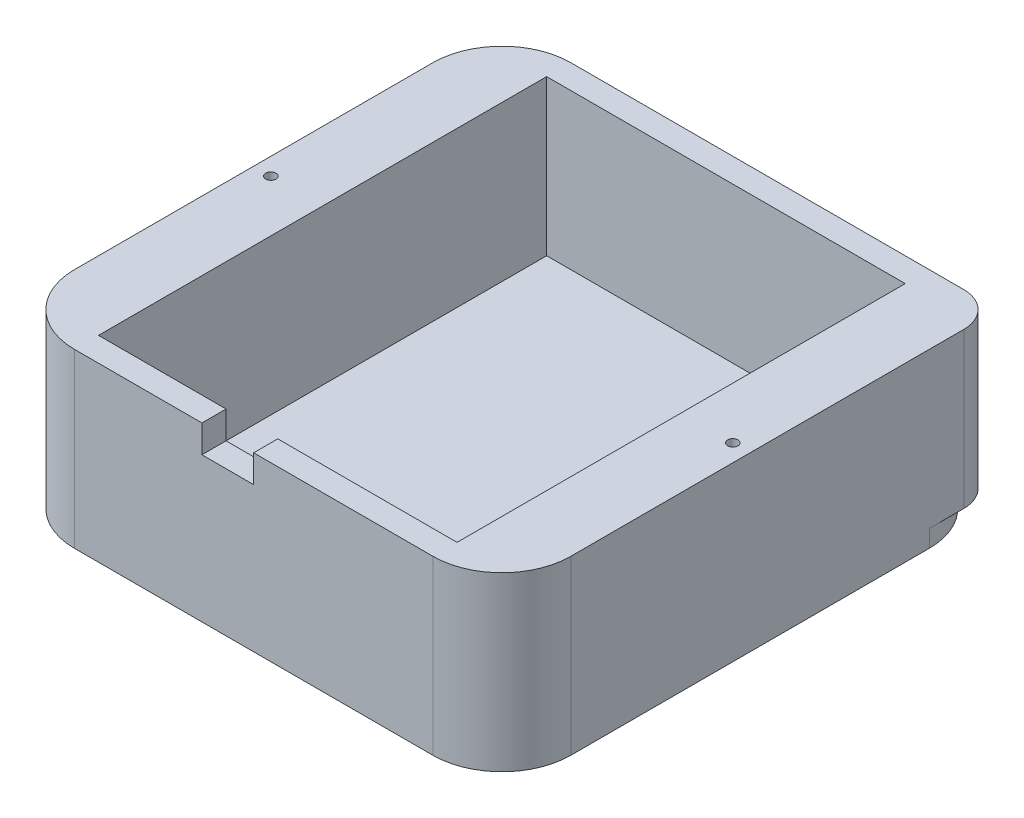
SolidWorks part; units mm, degrees
ref_plane "Front Plane" through (0, 0, 0) normal (0, 0, 1) x (1, 0, 0)
ref_plane "Top Plane" through (0, 0, 0) normal (0, 1, 0) x (1, 0, 0)
ref_plane "Right Plane" through (0, 0, 0) normal (1, 0, 0) x (0, 0, -1)
sketch "Sketch1" plane through (0, 0, 0) normal (0, 1, 0) x (1, 0, 0)
  line L1 (-72, 72) -> (72, 72)
  line L2 (-72, 72) -> (-72, -72)
  line L3 (-72, -72) -> (72, -72)
  line L4 (72, 72) -> (72, -72)
  point P0 (0, 0)
  dimension "D1" = 144
  dimension "D2" = 72
  dimension "D3" = 72
extrude "Boss-Extrude1" add sketch "Sketch1" along normal blind 5
fillet "Fillet1" radius 20 4 edges at (-72, 2.5, -72) (72, 2.5, -72) (-72, 2.5, 72) (72, 2.5, 72)
sketch "Sketch2" plane through (0, 5, 0) normal (0, 1, 0) x (1, 0, 0)
  line L0 (0, 72) -> (0, -72) construction
  line L2 (-52, -65) -> (-52, 65)
  line L3 (52, 72) -> (-52, 72) construction
  line L4 (-52, -72) -> (52, -72) construction
  line L5 (-72, 0) -> (72, 0) construction
  line L6 (-72, 52) -> (-72, -52) construction
  line L7 (72, -52) -> (72, 52) construction
  line L8 (52, -65) -> (52, 65)
  line L9 (-52, 65) -> (52, 65)
  line L10 (-52, -65) -> (52, -65)
  line L11 (-72, 52) -> (-72, -52)
  line L12 (72, 62) -> (72, -52)
  line L13 (52, -72) -> (-52, -72)
  line L14 (-52, 72) -> (62, 72)
  arc A0 (52, -72) -> (72, -52) centre (52, -52) ccw construction
  arc A1 (62, 72) -> (72, 62) centre (62, 62) cw
  arc A2 (-72, 52) -> (-52, 72) centre (-52, 52) cw
  arc A3 (-72, -52) -> (-52, -72) centre (-52, -52) ccw
  arc A4 (72, -52) -> (52, -72) centre (52, -52) cw
  point P17 (-52, 0)
  dimension "D1" = 52
  dimension "D3" = 10
  dimension "D2" = 65
extrude "Boss-Extrude2" add sketch "Sketch2" along normal blind 45
sketch "Sketch3" plane through (0, 50, 0) normal (0, 1, 0) x (1, 0, 0)
  circle A0 centre (-67, 0) radius 1.5
  circle A1 centre (67, 0) radius 1.5
  dimension "D1" = 3
  dimension "D3" = 3
  dimension "D2" = 67
  dimension "D4" = 67
extrude "Cut-Extrude1" cut sketch "Sketch3" against normal blind 13
sketch "Sketch5" plane through (0, 0, 72) normal (0, 0, 1) x (1, 0, 0)
  line L0 (0, 50) -> (-15, 50)
  line L1 (-52, 50) -> (52, 50) construction
  line L2 (-15, 50) -> (-15, 42)
  line L3 (-15, 42) -> (0, 42)
  line L4 (0, 42) -> (0, 50)
  dimension "D1" = 15
  dimension "D2" = 8
extrude "Cut-Extrude2" cut sketch "Sketch5" against normal blind 8
